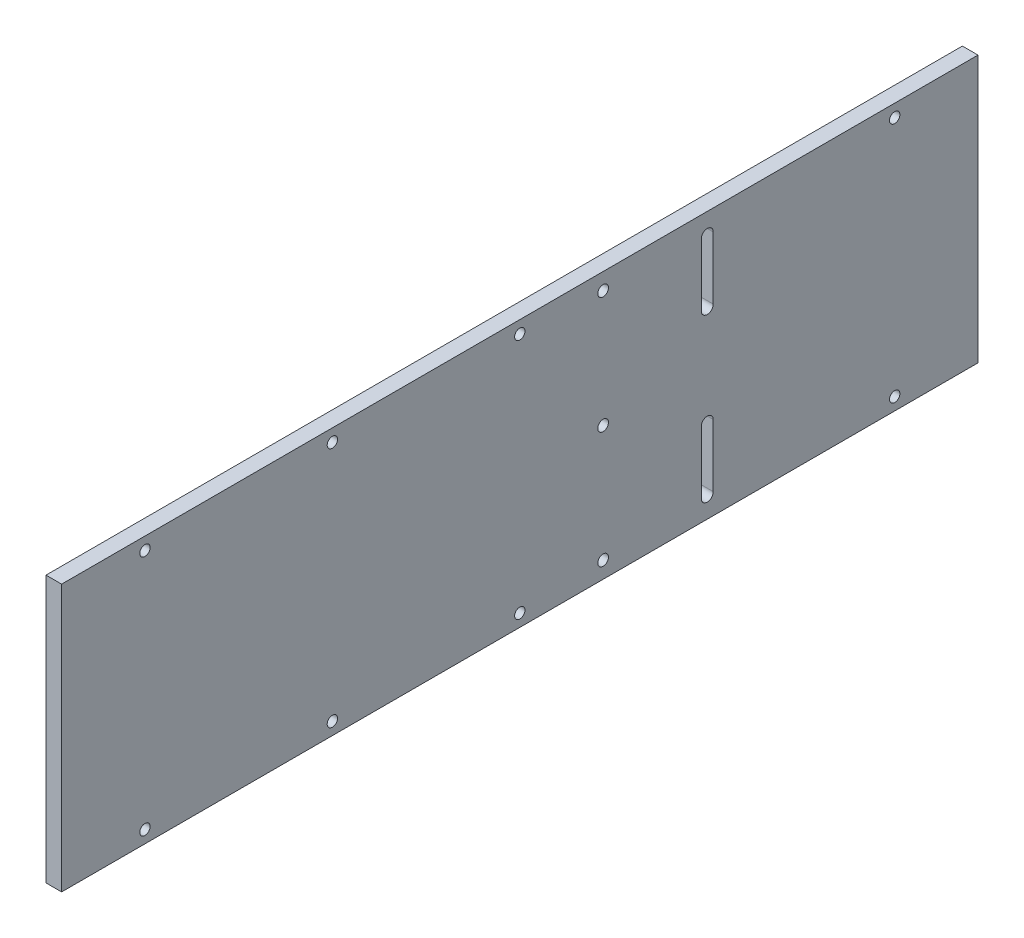
SolidWorks part; units mm, degrees
material "6061-T6 (SS)"
ref_plane "Front Plane" through (0, 0, 0) normal (0, 0, 1) x (1, 0, 0)
ref_plane "Top Plane" through (0, 0, 0) normal (0, 1, 0) x (1, 0, 0)
ref_plane "Right Plane" through (0, 0, 0) normal (1, 0, 0) x (0, 0, -1)
sketch "Sketch1" plane through (0, 0, 0) normal (1, 0, 0) x (0, 0, -1)
  line L0 (0, 12.7) -> (0, -12.7) construction
  line L1 (0, -12.7) -> (33.2976, -40.64) construction
  line L2 (33.2976, -40.64) -> (312.6976, -40.64)
  line L3 (312.6976, -40.64) -> (345.9952, -12.7) construction
  line L4 (345.9952, -12.7) -> (345.9952, 12.7) construction
  line L5 (345.9952, 12.7) -> (312.6976, 40.64) construction
  line L6 (312.6976, 40.64) -> (33.2976, 40.64)
  line L7 (33.2976, 40.64) -> (0, 12.7) construction
  line L8 (33.2976, 40.64) -> (33.2976, -40.64)
  line L9 (312.6976, 40.64) -> (312.6976, -40.64)
  line L10 (0, 0) -> (345.9952, 0) construction
  line L11 (0, 12.7) -> (-63.5681, -40.64) construction
  line L12 (-63.5681, -40.64) -> (33.2976, -40.64) construction
  line L13 (312.6976, 40.64) -> (409.5633, 40.64) construction
  line L14 (409.5633, 40.64) -> (345.9952, -12.7) construction
  point P10 (33.2976, 0)
  point P12 (312.6976, 0)
  dimension "D1" = 81.28
  dimension "D2" = 279.4
  dimension "D3" = 25.4
  dimension "D4" = 40
extrude "Boss-Extrude1" add sketch "Sketch1" along normal blind 4.7625
sketch "Sketch2" plane through (4.7625, 0, 0) normal (1, 0, 0) x (0, 0, -1)
  line L0 (-3.2177, 10) -> (373.048, 10) construction
  line L1 (312.6976, -40.64) -> (409.5633, 40.64) construction
  line L2 (345.048, 10) -> (245.048, 10) construction
  line L3 (245.048, -5) -> (345.048, -5) construction
  line L4 (245.048, -5) -> (245.048, 25) construction
  line L5 (245.048, 25) -> (345.048, 25) construction
  line L6 (345.048, -5) -> (345.048, 25) construction
  line L7 (33.2976, 40.64) -> (-63.5681, -40.64) construction
  line L9 (0, 0) -> (361.1305, 0) construction
  circle A0 centre (300.048, 10) radius 6.9977 construction
  circle A1 centre (282.2147, 8) radius 1.4986 construction
  circle A2 centre (270.2178, 15.9334) radius 0.9906 construction
  circle A3 centre (282.2147, 8) radius 11.4777 construction
  circle A4 centre (270.2178, 15.9334) radius 7.1501 construction
  circle A5 centre (300.048, 10) radius 12.827 construction
  circle A6 centre (261.048, 10) radius 14 construction
  circle A7 centre (282.2147, 8) radius 5.1181 construction
  circle A8 centre (331.0042, 10) radius 4.7625
  point P11 (300.048, 10)
  point P12 (282.2147, 8)
  point P13 (270.2178, 15.9334)
  point P23 (261.048, 10)
  dimension "D5" = 13.9954
  dimension "D6" = 2.9972
  dimension "D7" = 1.9812
  dimension "D8" = 25.654
  dimension "D9" = 22.9553
  dimension "D10" = 14.3002
  dimension "D12" = 28
  dimension "D13" = 10.2362
  dimension "D17" = 9.525
  dimension "D1" = 17.9451
  dimension "D2" = 14.3828
  dimension "D3" = 30
  dimension "D4" = 100
  dimension "D11" = 10.922
  dimension "D14" = 16
  dimension "D15" = 13
  dimension "D16" = 55
  dimension "D18" = 30.9562
  dimension "D19" = 28
  dimension "D20" = 10
extrude "Gearbox (with Press fits)" cut sketch "Sketch2" against normal through all
sketch "Sketch3" plane through (4.7625, 0, 0) normal (1, 0, 0) x (0, 0, -1)
  line L0 (0, 0) -> (361.1305, 0) construction
  line L1 (28.757, 36.83) -> (405.0227, 36.83) construction
  line L2 (230.1476, 36.83) -> (230.1476, -36.83) construction
  line L3 (230.1476, 34.29) -> (230.1476, 15.24) construction
  line L4 (33.2976, 40.64) -> (-63.5681, -40.64) construction
  line L5 (312.6976, 40.64) -> (33.2976, 40.64) construction
  line L6 (312.6976, -40.64) -> (409.5633, 40.64) construction
  line L7 (231.9764, 34.29) -> (231.9764, 15.24)
  line L8 (228.3188, 34.29) -> (228.3188, 15.24)
  line L10 (230.1476, -34.29) -> (230.1476, -15.24) construction
  line L11 (231.9764, -34.29) -> (231.9764, -15.24)
  line L12 (228.3188, -34.29) -> (228.3188, -15.24)
  line L13 (312.6976, -40.64) -> (312.6976, 40.64) construction
  line L15 (312.6976, 40.64) -> (33.2976, 40.64) construction
  circle A0 centre (287.2976, 36.83) radius 1.5811
  circle A1 centre (230.1476, 36.83) radius 1.5811 construction
  circle A2 centre (172.9976, 36.83) radius 1.5811
  circle A3 centre (115.8476, 36.83) radius 1.5811
  circle A4 centre (58.6976, 36.83) radius 1.5812
  circle A5 centre (58.6976, -36.83) radius 1.5812
  circle A6 centre (115.8476, -36.83) radius 1.5811
  circle A7 centre (172.9976, -36.83) radius 1.5811
  circle A8 centre (230.1476, -36.83) radius 1.5811 construction
  circle A9 centre (287.2976, -36.83) radius 1.5811
  arc A10 (231.9764, 34.29) -> (228.3188, 34.29) centre (230.1476, 34.29) ccw
  arc A11 (228.3188, 15.24) -> (231.9764, 15.24) centre (230.1476, 15.24) ccw
  arc A12 (231.9764, -34.29) -> (228.3188, -34.29) centre (230.1476, -34.29) cw
  arc A13 (228.3188, -15.24) -> (231.9764, -15.24) centre (230.1476, -15.24) cw
  point P32 (230.1476, 24.765)
  point P43 (230.1476, -24.765)
  dimension "D1" = 3.1623
  dimension "D2" = 25.4
  dimension "D6" = 6.35
  dimension "D4" = 3.81
  dimension "D5" = 3.6576
  dimension "D7" = 19.05
  dimension "D3" = 5
extrude "Cut-Extrude1" cut sketch "Sketch3" against normal through all
hole_wizard "#4 Clearance Hole1" positions "Sketch10" profile "Sketch8" hole size "#4" standard "ANSI Inch"
sketch "Sketch10" plane through (4.7625, 0, 0) normal (1, 0, 0) x (0, 0, -1)
  line L0 (27.2435, 35.56) -> (403.5092, 35.56) construction
  line L1 (33.2976, 40.64) -> (-63.5681, -40.64) construction
  line L3 (312.6976, -40.64) -> (409.5633, 40.64) construction
  line L4 (-15.1353, 0) -> (361.1305, 0) construction
  line L6 (409.5633, 40.64) -> (33.2976, 40.64) construction
  line L7 (198.3976, 35.56) -> (198.3976, -35.56) construction
  point P16 (198.3976, 35.56)
  point P19 (198.3976, -35.56)
  point P24 (198.3976, 0)
  dimension "D1" = 5.08
  dimension "D2" = 165.1
sketch "Sketch8" plane through (4.7625, 35.56, -198.3976) normal (0, 1, 0) x (0, 0, -1)
  line L0 (0, 0) -> (0, 5.8066)
  line L1 (0, 5.8066) -> (1.6319, 4.826)
  line L2 (1.6319, 4.826) -> (1.6319, 0)
  line L5 (1.6319, 0) -> (0, 0)
  line L10 (0, 5.8066) -> (-1.6319, 4.826) construction
  line L11 (0, -6.35) -> (0, 107.95) construction
  dimension "Hole Dia." = 3.2639
  dimension "Hole Depth" = 4.826
  dimension "Drill Angle" = 118
sketch "Sketch11" plane through (4.7625, 0, 0) normal (1, 0, 0) x (0, 0, -1)
  line L0 (18.1623, 27.94) -> (394.4281, 27.94) construction
  line L1 (33.2976, 40.64) -> (-63.5681, -40.64) construction
  line L2 (312.6976, -40.64) -> (409.5633, 40.64) construction
  line L3 (-48.4329, -27.94) -> (327.8329, -27.94) construction
  line L4 (-21.9928, -22.3328) -> (35.7449, 26.1148)
  line L5 (39.9758, 25.9814) -> (90.8271, -22.4663)
  line L6 (88.637, -27.94) -> (-19.9519, -27.94)
  line L7 (62.0768, 22.4663) -> (112.7937, -25.8534)
  line L8 (117.1739, -25.8534) -> (167.8909, 22.4663)
  line L9 (165.7008, 27.94) -> (64.2668, 27.94)
  line L10 (186.6825, 22.8285) -> (139.1405, -22.4663)
  line L11 (141.3306, -27.94) -> (188.8726, -27.94)
  line L12 (192.0476, -24.765) -> (192.0476, 20.5298)
  line L13 (204.7476, 18.9322) -> (204.7476, -24.765)
  line L14 (409.5633, 40.64) -> (33.2976, 40.64) construction
  line L15 (-63.5681, -40.64) -> (312.6976, -40.64) construction
  line L16 (207.9226, -27.94) -> (243.0966, -27.94)
  line L17 (245.5699, -22.7741) -> (210.3959, 20.9231)
  line L18 (225.2091, 22.7741) -> (263.9995, -25.4158)
  line L19 (268.5136, -25.8571) -> (325.9442, 22.3328)
  line L20 (323.9033, 27.94) -> (227.6824, 27.94)
  line L21 (114.9838, 27.94) -> (114.9838, -27.94) construction
  circle A0 centre (198.3976, 0) radius 6.35 construction
  arc A1 (188.8726, -27.94) -> (192.0476, -24.765) centre (188.8726, -24.765) ccw
  arc A2 (139.1405, -22.4663) -> (141.3306, -27.94) centre (141.3306, -24.765) ccw
  arc A3 (192.0476, 20.5298) -> (186.6825, 22.8285) centre (188.8726, 20.5298) ccw
  arc A4 (167.8909, 22.4663) -> (165.7008, 27.94) centre (165.7008, 24.765) ccw
  arc A5 (62.0768, 22.4663) -> (64.2668, 27.94) centre (64.2668, 24.765) cw
  arc A6 (112.7937, -25.8534) -> (117.1739, -25.8534) centre (114.9838, -23.5547) ccw
  arc A7 (90.8271, -22.4663) -> (88.637, -27.94) centre (88.637, -24.765) cw
  arc A8 (35.7449, 26.1148) -> (39.9758, 25.9814) centre (37.7857, 23.6826) cw
  arc A9 (-21.9928, -22.3328) -> (-19.9519, -27.94) centre (-19.9519, -24.765) ccw
  circle A10 centre (331.0042, 10) radius 12.7 construction
  arc A11 (325.9442, 22.3328) -> (323.9033, 27.94) centre (323.9033, 24.765) ccw
  arc A12 (225.2091, 22.7741) -> (227.6824, 27.94) centre (227.6824, 24.765) cw
  arc A13 (263.9995, -25.4158) -> (268.5136, -25.8571) centre (266.4728, -23.4249) ccw
  arc A14 (243.0966, -27.94) -> (245.5699, -22.7741) centre (243.0966, -24.765) ccw
  arc A15 (204.7476, -24.765) -> (207.9226, -27.94) centre (207.9226, -24.765) ccw
  arc A16 (204.7476, 18.9322) -> (210.3959, 20.9231) centre (207.9226, 18.9322) cw
  point P26 (192.0476, -27.94)
  point P29 (133.3952, -27.94)
  point P32 (192.0476, 27.94)
  point P35 (173.6362, 27.94)
  point P38 (56.3315, 27.94)
  point P41 (114.9838, -27.94)
  point P44 (96.5724, -27.94)
  point P47 (37.92, 27.94)
  point P50 (-28.6752, -27.94)
  point P62 (332.6266, 27.94)
  point P65 (221.0509, 27.94)
  point P68 (266.0314, -27.94)
  point P71 (249.7281, -27.94)
  point P74 (204.7476, -27.94)
  point P77 (204.7476, 27.94)
  dimension "D3" = 12.7
  dimension "D7" = 3.175
  dimension "D9" = 25.4
  dimension "D10" = 3.175
  dimension "D1" = 12.7
  dimension "D2" = 12.7
  dimension "D4" = 12.7
  dimension "D5" = 12.7
  dimension "D6" = 12.7
  dimension "D8" = 12.7
extrude "Cut-Extrude2" [suppressed] cut sketch "Sketch11" against normal through all
